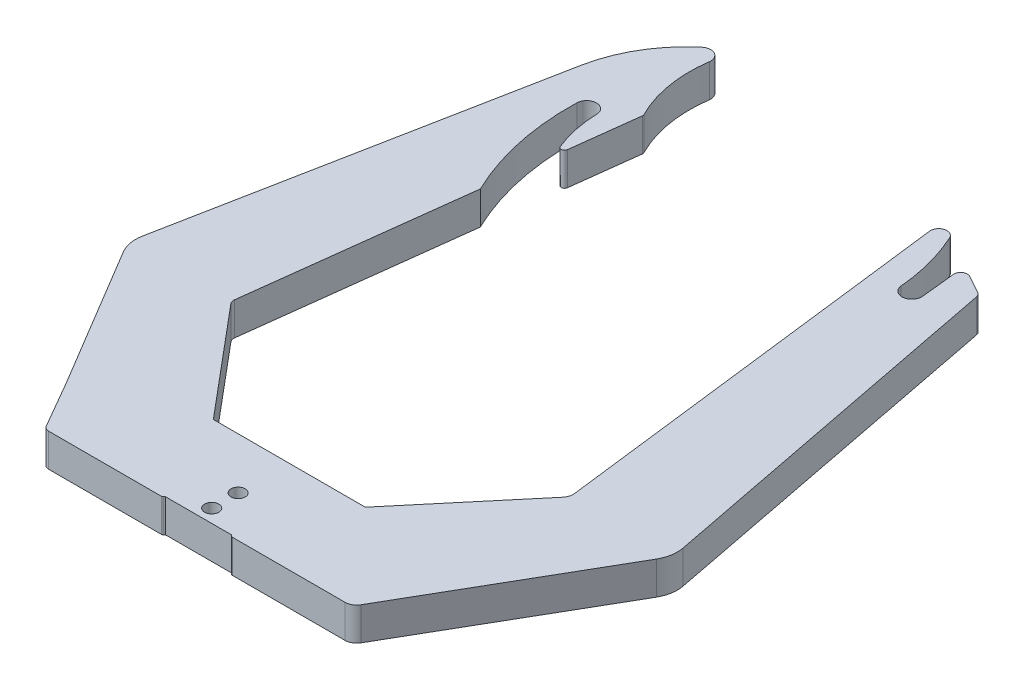
SolidWorks part; units mm, degrees
ref_plane "前视基准面" through (0, 0, 0) normal (0, 0, 1) x (1, 0, 0)
ref_plane "上视基准面" through (0, 0, 0) normal (0, 1, 0) x (1, 0, 0)
ref_plane "右视基准面" through (0, 0, 0) normal (1, 0, 0) x (0, 0, -1)
sketch "草图1" plane through (0, 0, 0) normal (0, 1, 0) x (1, 0, 0)
  line L0 (0, 0) -> (0, -28) construction
  line L1 (-23, 0) -> (23, 0)
  line L2 (-46.9045, -28) -> (46.9045, -28) construction
  line L3 (23, 0) -> (50.2858, 32.5179)
  line L4 (51.0937, 35.2452) -> (36.049, 157.7742)
  line L5 (47.9341, -26.2167) -> (80.661, 30.468)
  line L6 (81.8171, 37.3761) -> (60.3838, 147.6409)
  line L7 (-10, -27.5) -> (10, -27.5)
  line L8 (10, -27.5) -> (10.3536, -27.8536)
  line L9 (10.7071, -28) -> (44.8453, -28)
  line L10 (-10, -27.5) -> (-10.3536, -27.8536)
  line L11 (-10.7071, -28) -> (-44.8453, -28)
  line L12 (-46.9045, -28) -> (-80.661, 30.468) construction
  line L13 (-23, 0) -> (-50.7237, 33.0398)
  line L14 (-51.2827, 33.706) -> (-36.049, 157.7742) construction
  line L15 (-81.8171, 37.3761) -> (-60.2058, 148.5563)
  line L16 (52.0766, 139.6979) -> (50.9866, 150.0683)
  line L17 (53.9453, 152.0266) -> (59.3901, 149.0085)
  line L18 (-37.6333, 144.8711) -> (-51.1767, 34.5691)
  line L26 (-80.661, 30.468) -> (-54.7279, -12.8828)
  line L27 (-54.7279, -12.8828) -> (-46.5774, -27)
  arc A0 (80.661, 30.468) -> (81.8171, 37.3761) centre (72.0008, 35.468) ccw
  arc A1 (-80.661, 30.468) -> (-81.8171, 37.3761) centre (-72.0008, 35.468) cw
  arc A2 (36.049, 157.7742) -> (40.8001, 159.1268) centre (38.5304, 158.0789) cw
  arc A3 (40.8001, 159.1268) -> (46.1041, 139.1268) centre (-13.6745, 133.977) cw
  arc A4 (46.1041, 139.1268) -> (52.0766, 139.6979) centre (49.093, 139.3843) ccw
  arc A5 (60.3838, 147.6409) -> (59.3901, 149.0085) centre (58.4205, 147.2592) ccw
  arc A6 (50.9866, 150.0683) -> (53.9453, 152.0266) centre (52.9756, 150.2774) cw
  arc A7 (-60.2058, 148.5563) -> (-46.6224, 171.5908) centre (-20.9407, 140.924) cw
  arc A8 (-46.6224, 171.5908) -> (-41.7258, 168.8711) centre (-44.6963, 169.2908) cw
  arc A9 (-41.7258, 168.8711) -> (-37.6333, 144.8711) centre (-2.119, 163.2759) ccw
  arc A10 (-50.7237, 33.0398) -> (-51.1767, 34.5691) centre (-49.1916, 34.3254) cw
  arc A19 (47.9341, -26.2167) -> (44.8453, -28) centre (44.8453, -24.4333) cw
  arc A20 (50.2858, 32.5179) -> (51.0937, 35.2452) centre (47.5536, 34.8106) ccw
  arc A21 (10.3536, -27.8536) -> (10.7071, -28) centre (10.7071, -27.5) ccw
  arc A22 (-10.3536, -27.8536) -> (-10.7071, -28) centre (-10.7071, -27.5) cw
  arc A23 (-44.8453, -28) -> (-46.5774, -27) centre (-44.8453, -26) cw
  point P7 (0, 0)
  point P9 (0, -28)
  point P18 (82.5305, 33.706)
  point P24 (0, -27.5)
  point P36 (0, 0)
  point P37 (50.2421, 139.678)
  point P38 (49.093, 139.3843)
  point P50 (60.2058, 148.5563)
  point P53 (50.585, 153.8892)
  point P76 (-54.639, -14.6035)
  point P85 (51.2827, 33.706)
  point P88 (10.5, -28)
  point P91 (-10.5, -28)
  dimension "D14" = 10
  dimension "D17" = 2.5
  dimension "D18" = 3
  dimension "D20" = 60
  dimension "D22" = 2
  dimension "D23" = 40
  dimension "D24" = 3
  dimension "D26" = 40
  dimension "D30" = 2
  dimension "D39" = 0.5
  dimension "D28" = 2
  dimension "D1" = 28
  dimension "D2" = 46
  dimension "D4" = 130
  dimension "D5" = 44
  dimension "D6" = 133
  dimension "D7" = 125
  dimension "D8" = 120
  dimension "D9" = 139
  dimension "D10" = 117
  dimension "D11" = 10
  dimension "D12" = 1
  dimension "D13" = 135
  dimension "D15" = 130
  dimension "D16" = 55
  dimension "D19" = 20
  dimension "D21" = 11
  dimension "D25" = 13
  dimension "D27" = 24
  dimension "D29" = 34.1382
  dimension "D31" = 34.1382
extrude "凸台-拉伸1" add sketch "草图1" along normal blind 10
sketch "草图2" plane through (0, 10, 0) normal (0, 1, 0) x (1, 0, 0)
  line L0 (-51.1767, 34.5691) -> (-37.6333, 144.8711) construction
  line L2 (-40.5801, 120.8711) -> (-43.0358, 100.8711)
  line L3 (-10, -27.5) -> (10, -27.5) construction
  line L4 (23, 0) -> (-23, 0) construction
  arc A0 (-43.0358, 100.8711) -> (-50.9987, 138.0882) centre (28.9667, 135.7371) cw
  arc A1 (-50.9987, 138.0882) -> (-45.0011, 138.0823) centre (-48, 138) cw
  arc A2 (-45.0011, 138.0823) -> (-40.5801, 120.8711) centre (-5.0162, 139.1798) ccw
  circle A3 centre (0, -23.5) radius 2.15
  circle A4 centre (0, -15.5) radius 2.15
  dimension "D5" = 3
  dimension "D6" = 138
  dimension "50" = 40
  dimension "D7" = 80
  dimension "D9" = 4.3
  dimension "D2" = 20
  dimension "D3" = 24
  dimension "D4" = 48
  dimension "D8" = 8
  dimension "D10" = 4
extrude "切除-拉伸1" cut sketch "草图2" against normal up to next
fillet "圆角1" radius 1 2 edges at (-37.6333, 5, -144.8711) (-40.5801, 5, -120.8711)
